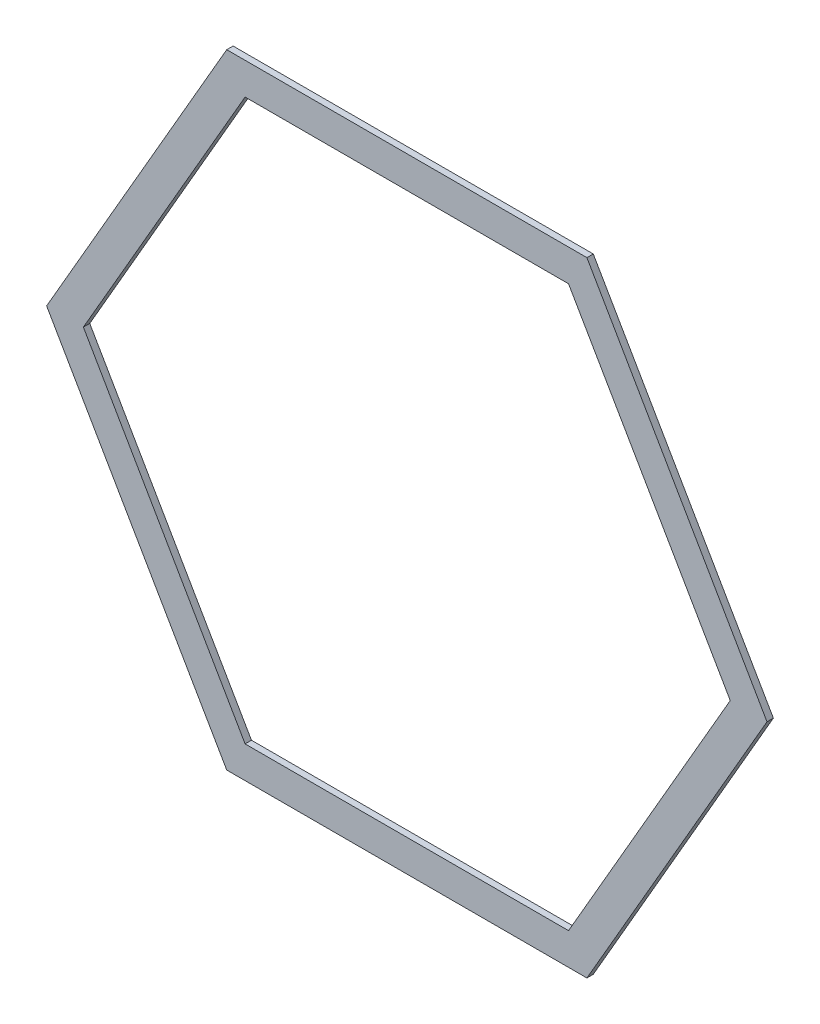
SolidWorks part; units mm, degrees
ref_plane "Plan de face" through (0, 0, 0) normal (0, 0, 1) x (1, 0, 0)
ref_plane "Plan de dessus" through (0, 0, 0) normal (0, 1, 0) x (1, 0, 0)
ref_plane "Plan de droite" through (0, 0, 0) normal (1, 0, 0) x (0, 0, -1)
sketch "Esquisse1" plane through (0, 0, 0) normal (0, 0, 1) x (1, 0, 0)
  line L1 (56.5803, 0) -> (28.2902, 49)
  line L2 (28.2902, 49) -> (-28.2902, 49)
  line L3 (-28.2902, 49) -> (-56.5803, 0)
  line L4 (-56.5803, 0) -> (-28.2902, -49)
  line L5 (-28.2902, -49) -> (28.2902, -49)
  line L6 (28.2902, -49) -> (56.5803, 0)
  line L7 (50.8068, 0) -> (25.4034, 44)
  line L8 (25.4034, 44) -> (-25.4034, 44)
  line L9 (-25.4034, 44) -> (-50.8068, 0)
  line L10 (-50.8068, 0) -> (-25.4034, -44)
  line L11 (-25.4034, -44) -> (25.4034, -44)
  line L12 (25.4034, -44) -> (50.8068, 0)
  circle A0 centre (0, 0) radius 49 construction
  circle A1 centre (0, 0) radius 44 construction
  dimension "D1" = 98
  dimension "D2" = 5
extrude "Boss.-Extru.1" add sketch "Esquisse1" along normal blind 1
